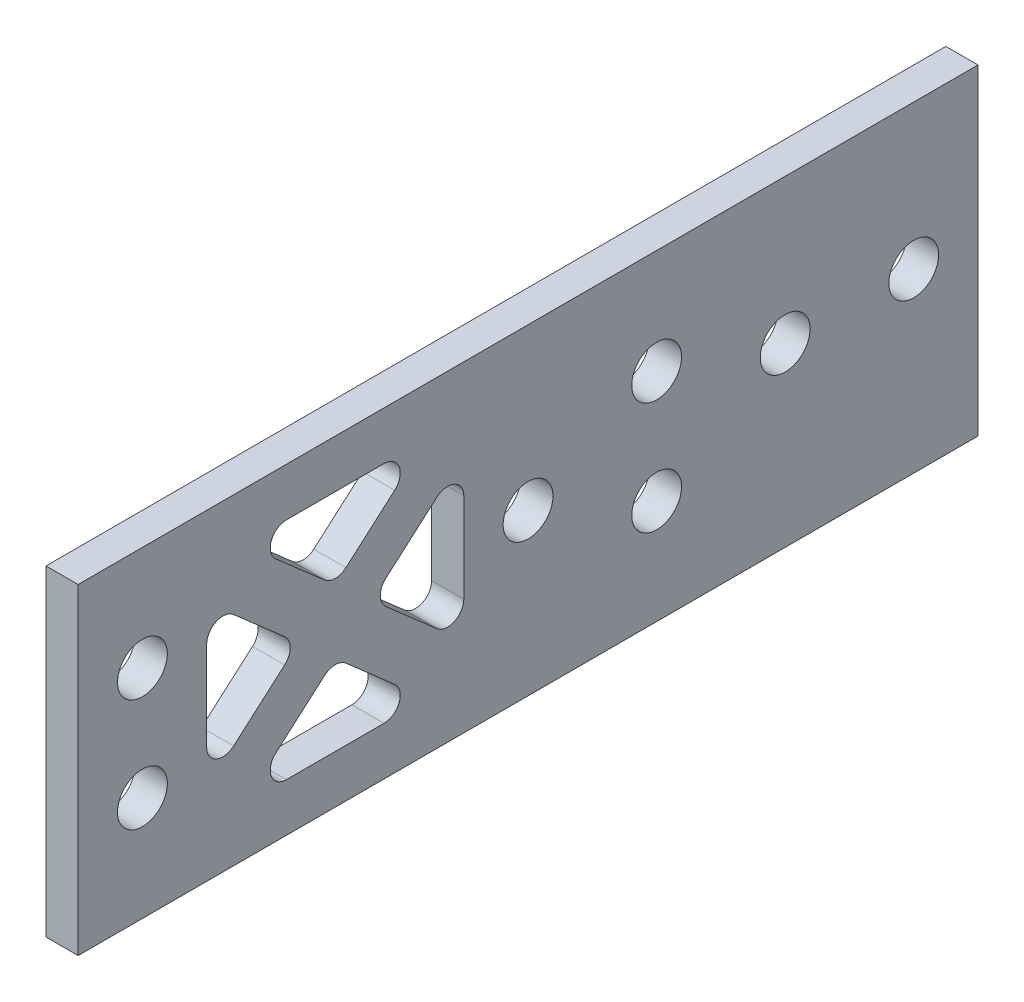
SolidWorks part; units mm, degrees
material "Thornel Mat VMA"
ref_plane "前视基准面" through (0, 0, 0) normal (0, 0, 1) x (1, 0, 0)
ref_plane "上视基准面" through (0, 0, 0) normal (0, 1, 0) x (1, 0, 0)
ref_plane "右视基准面" through (0, 0, 0) normal (1, 0, 0) x (0, 0, -1)
sketch "草图1" plane through (0, 0, 0) normal (1, 0, 0) x (0, 0, -1)
  line L0 (0, 0) -> (9.198, 0) construction
  line L1 (20, -10) -> (-20, -10)
  line L2 (20, -10) -> (20, 10) construction
  line L3 (20, 10) -> (-20, 10)
  line L4 (-20, -10) -> (-20, 10)
  line L5 (20, -10) -> (-20, 10) construction
  line L6 (20, 10) -> (-20, -10) construction
  line L7 (0, 0) -> (0, 7.0347) construction
  line L8 (-12, -5.0068) -> (-6.2779, 0)
  line L13 (4, -7) -> (-12, -7) construction
  line L14 (4, -7) -> (4, 7) construction
  line L15 (4, 7) -> (-12, 7) construction
  line L16 (-12, -7) -> (-12, 7) construction
  line L17 (4, -7) -> (-12, 7) construction
  line L18 (4, 7) -> (-12, -7) construction
  line L19 (-9.7221, -7) -> (-4, -1.9932)
  line L20 (-9.7221, 7) -> (-4, 1.9932)
  line L21 (-12, 5.0068) -> (-6.2779, 0)
  line L22 (-9.7221, 7) -> (1.7221, 7)
  line L23 (4, 5.0068) -> (4, -5.0068)
  line L24 (-9.7221, -7) -> (1.7221, -7)
  line L25 (-12, 5.0068) -> (-12, -5.0068)
  line L26 (-4, 1.9932) -> (1.7221, 7)
  line L27 (-1.7221, 0) -> (4, -5.0068)
  line L28 (-1.7221, 0) -> (4, 5.0068)
  line L29 (-4, -1.9932) -> (1.7221, -7)
  line L30 (20, 10) -> (36, 10)
  line L31 (36, 10) -> (36, -10)
  line L32 (36, -10) -> (20, -10)
  circle A0 centre (8, 0) radius 1.55
  circle A1 centre (16, 3.5) radius 1.55
  circle A2 centre (16, -3.5) radius 1.55
  circle A3 centre (-16, -3.5) radius 1.55
  circle A4 centre (-16, 3.5) radius 1.55
  circle A5 centre (24, 1) radius 1.55
  circle A6 centre (32, 1) radius 1.55
  point P0 (0, 0)
  point P21 (-4, 0)
  dimension "D3" = 3.1
  dimension "D12" = 3.1
  dimension "D1" = 20
  dimension "D2" = 40
  dimension "D4" = 7
  dimension "D5" = 8
  dimension "D6" = 4
  dimension "D7" = 3
  dimension "D8" = 4
  dimension "D9" = 4
  dimension "D10" = 8
  dimension "D11" = 3
  dimension "D13" = 8
  dimension "D14" = 4
  dimension "D15" = 1
extrude "凸台-拉伸1" add sketch "草图1" along normal blind 2
fillet "圆角1" radius 1.01 12 edges at (1, -5.0068, -4) (1, 5.0068, -4) (1, 0, 1.7221) (1, -1.9932, 4) (1, -7, 9.7221) (1, -7, -1.7221) (1, -5.0068, 12) (1, 1.9932, 4) (1, 7, -1.7221) (1, 7, 9.7221) (1, 0, 6.2779) (1, 5.0068, 12)
